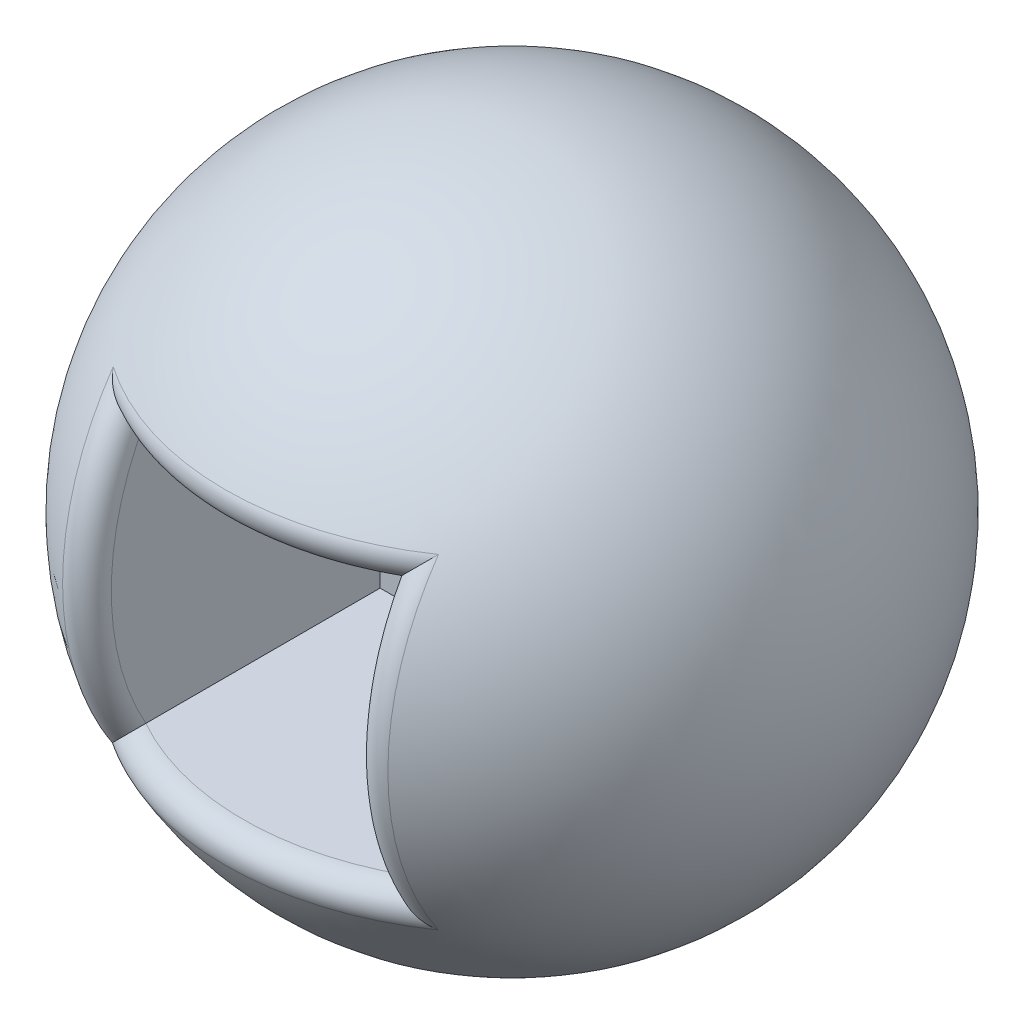
SolidWorks part; units mm, degrees
ref_plane "정면" through (0, 0, 0) normal (0, 0, 1) x (1, 0, 0)
ref_plane "윗면" through (0, 0, 0) normal (0, 1, 0) x (1, 0, 0)
ref_plane "우측면" through (0, 0, 0) normal (1, 0, 0) x (0, 0, -1)
sketch "스케치1" plane through (0, 0, 0) normal (0, 0, 1) x (1, 0, 0)
  line L0 (0, 8) -> (0, -8)
  arc A0 (0, -8) -> (0, 8) centre (0, 0) ccw
  dimension "D1" = 16
revolve "회전2" add sketch "스케치1" angle 360 about L0
ref_plane "평면1" through (0, 0, 8) normal (0, 0, 1) x (1, 0, 0)
sketch "스케치2" plane through (0, 0, 8) normal (0, 0, 1) x (1, 0, 0)
  line L1 (-3.2, 3.2) -> (3.2, 3.2)
  line L2 (-3.2, 3.2) -> (-3.2, -3.2)
  line L3 (-3.2, -3.2) -> (3.2, -3.2)
  line L4 (3.2, 3.2) -> (3.2, -3.2)
  point P7 (0, 3.2)
  point P9 (3.2, 0)
  dimension "D1" = 6.4
extrude "컷-돌출1" cut sketch "스케치2" along direction (0, 0, 1) on the side against the normal up to surface (8 mm away) up to plane "정면"
fillet "필렛1" radius 0.5 4 edges at (0, -3.2, 7.3321) (3.2, 0, 7.3321) (-3.2, 0, 7.3321) (0, 3.2, 7.3321)
